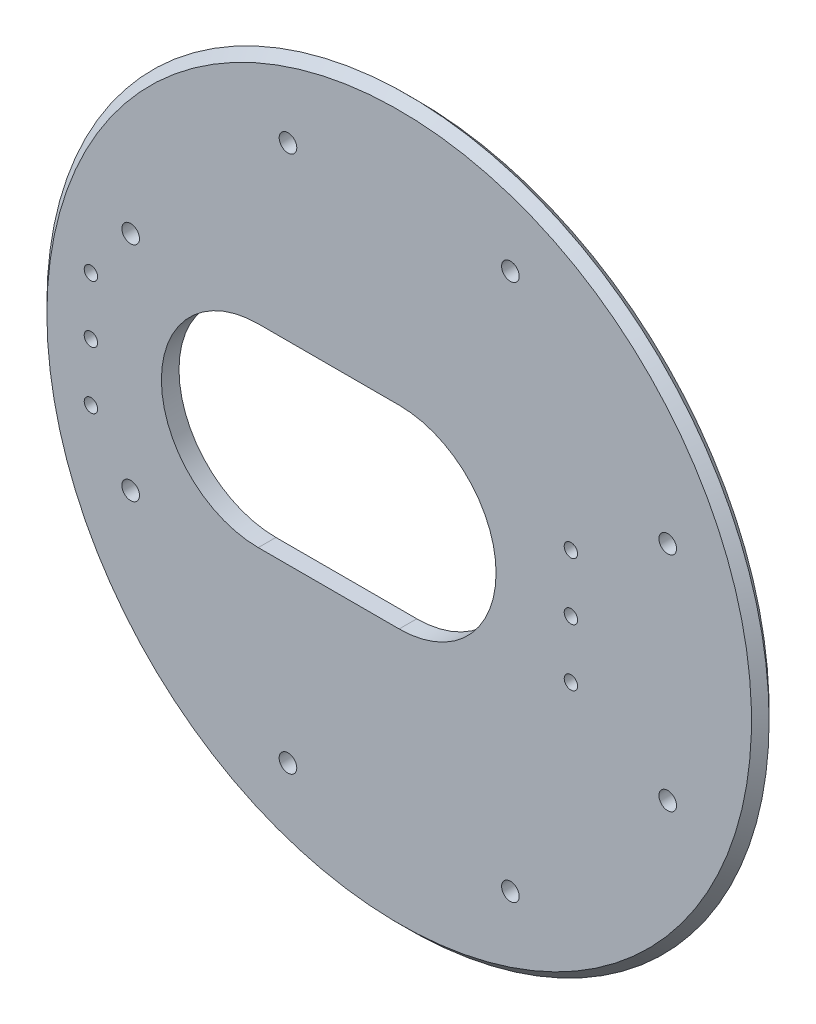
SolidWorks part; units mm, degrees
material "Chrome Stainless Steel"
ref_plane "Front Plane" through (0, 0, 0) normal (0, 0, 1) x (1, 0, 0)
ref_plane "Top Plane" through (0, 0, 0) normal (0, 1, 0) x (1, 0, 0)
ref_plane "Right Plane" through (0, 0, 0) normal (1, 0, 0) x (0, 0, -1)
sketch "Sketch1" plane through (0, 0, 0) normal (0, 0, 1) x (1, 0, 0)
  line L0 (0, 0) -> (-50.8, 0) construction
  line L1 (38.1, -38.1) -> (-38.1, -38.1)
  line L2 (38.1, -38.1) -> (38.1, 38.1)
  line L3 (38.1, 38.1) -> (-38.1, 38.1)
  line L4 (-38.1, -38.1) -> (-38.1, 38.1)
  line L5 (38.1, -38.1) -> (-38.1, 38.1) construction
  line L6 (38.1, 38.1) -> (-38.1, -38.1) construction
  line L7 (0, 0) -> (-63.5, 0) construction
  line L8 (-12.7, 38.1) -> (-88.9, 38.1)
  line L9 (-12.7, 38.1) -> (-12.7, -38.1)
  line L10 (-12.7, -38.1) -> (-88.9, -38.1)
  line L11 (-88.9, 38.1) -> (-88.9, -38.1)
  line L12 (-12.7, 38.1) -> (-88.9, -38.1) construction
  line L13 (-12.7, -38.1) -> (-88.9, 38.1) construction
  line L14 (-50.8, 34.925) -> (12.7, 34.925)
  line L15 (-50.8, -34.925) -> (12.7, -34.925)
  circle A0 centre (0, 0) radius 152.4
  arc A1 (-88.9, 38.1) -> (-88.9, -38.1) centre (-88.9, 0) ccw
  arc A2 (0, 38.1) -> (0, -38.1) centre (0, 0) cw
  circle A3 centre (0, 0) radius 34.925
  circle A4 centre (-50.8, 0) radius 34.925
  dimension "D1" = 304.8
  dimension "D7" = 69.85
  dimension "D9" = 69.85
  dimension "D2" = 76.2
  dimension "D3" = 76.2
  dimension "D4" = 50.8
  dimension "D5" = 76.2
  dimension "D6" = 76.2
  dimension "D8" = 63.5
extrude "Boss-Extrude1" add sketch "Sketch1" along normal blind 6.35 contours A0 L11 L8 L3 L2 L1 L10 | L3 A2 L2 | L2 A2 L1 | L11 A1 | A4 L14 L4 L8 L11 L10 L15 | A3 L15 L9 L1 A2 L3 L14 | L15 L4 L1 L9 | L4 L14 L9 L3
sketch "Sketch2" plane through (0, 0, 0) normal (0, 0, -1) x (-1, 0, 0)
  line L0 (85.725, 0) -> (111.125, 0) construction
  line L1 (111.125, 0) -> (111.125, -20.6375) construction
  line L2 (111.125, 20.6375) -> (111.125, 0) construction
  arc A0 (50.8, -34.925) -> (50.8, 34.925) centre (50.8, 0) ccw construction
  circle A1 centre (0, 0) radius 152.4
  circle A2 centre (0, 0) radius 152.4
  circle A5 centre (111.125, 20.6375) radius 2.413
  circle A6 centre (111.125, 0) radius 2.413
  circle A7 centre (111.125, -20.6375) radius 2.413
  dimension "D2" = 60.325
  dimension "D3" = 20.6375
  dimension "D4" = 20.6375
  dimension "D1" = 0
extrude "Cut-Extrude1" cut sketch "Sketch2" against normal blind 10.16 contours A5 | A6 | A7
sketch "Sketch4" plane through (0, 0, 6.35) normal (0, 0, 1) x (1, 0, 0)
  circle A3 centre (61.8998, 20.6375) radius 2.413
  circle A4 centre (61.8998, 0) radius 2.413
  circle A5 centre (61.8998, -20.6375) radius 2.413
  circle A7 centre (0, 0) radius 152.4
  circle A8 centre (0, 0) radius 152.4
  dimension "D1" = 0
extrude "Cut-Extrude2" cut sketch "Sketch4" against normal blind 7.62 contours A3 | A4 | A5
chamfer "Chamfer1" distance 2.54 angle 41 6 edges at (-113.538, -20.6375, 0) (-113.538, 0, 0) (-113.538, 20.6375, 0) (64.3128, -20.6375, 0) (64.3128, 0, 0) (64.3128, 20.6375, 0)
sketch "Sketch6" plane through (0, 0, 0) normal (0, 0, -1) x (-1, 0, 0)
  circle A0 centre (0, 0) radius 127
  circle M11 centre (0, 0) radius 152.4
  dimension "D1" = 254
extrude "Cut-Extrude3" cut sketch "Sketch6" against normal blind 7.62 contours A0 M11
sketch "Sketch5" plane through (0, 0, 0) normal (0, 1, 0) x (1, 0, 0)
  line L0 (-127, -6.35) -> (-127, 0)
  line L1 (-127, 0) -> (-130.175, -3.175)
  line L2 (-130.175, -3.175) -> (-127, -6.35)
  line L3 (0, 0) -> (0, -63.9389) construction
  line L5 (-127, 0) -> (-127, -6.35) construction
  line L6 (-127, -6.35) -> (127, -6.35) construction
  line L7 (127, 0) -> (-127, 0) construction
revolve "Revolve1" add sketch "Sketch5" angle 360 about L3
sketch "Sketch7" plane through (0, 0, 0) normal (0, 0, -1) x (-1, 0, 0)
  line L0 (0, 104.775) -> (0, 0) construction
  line L1 (0, 0) -> (40.0957, 96.7995) construction
  circle A0 centre (0, 0) radius 104.775 construction
  circle A1 centre (40.0957, 96.7995) radius 3.175
  circle A2 centre (96.7995, 40.0957) radius 3.175
  circle A3 centre (96.7995, -40.0957) radius 3.175
  circle A4 centre (40.0957, -96.7995) radius 3.175
  circle A5 centre (-40.0957, -96.7995) radius 3.175
  circle A6 centre (-96.7995, -40.0957) radius 3.175
  circle A7 centre (-96.7995, 40.0957) radius 3.175
  circle A8 centre (-40.0957, 96.7995) radius 3.175
  point P23 (0, 0)
  dimension "D1" = 209.55
  dimension "D2" = 22.5
  dimension "D3" = 6.35
  dimension "D4" = 8
extrude "Cut-Extrude4" cut sketch "Sketch7" against normal blind 15.24
